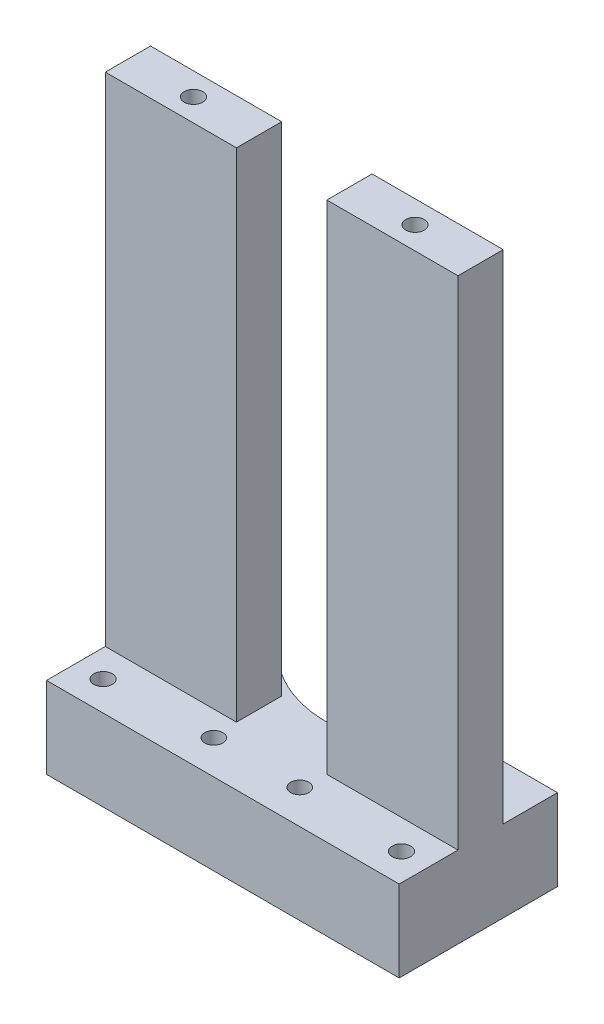
SolidWorks part; units mm, degrees
ref_plane "Ön Düzlem" through (0, 0, 0) normal (0, 0, 1) x (1, 0, 0)
ref_plane "Üst Düzlem" through (0, 0, 0) normal (0, 1, 0) x (1, 0, 0)
ref_plane "Sağ Düzlem" through (0, 0, 0) normal (1, 0, 0) x (0, 0, -1)
sketch "Çizim1" plane through (0, 0, 0) normal (0, 1, 0) x (1, 0, 0)
  line L3 (-39, 15) -> (-22, 15)
  line L5 (-39, 15) -> (-39, -20)
  line L6 (-39, -20) -> (39, -20)
  line L7 (39, 15) -> (39, -20)
  line L12 (22, 15) -> (39, 15)
  circle A0 centre (-29, 8) radius 2
  circle A1 centre (29, 8) radius 2
  arc A3 (-22, 15) -> (22, 15) centre (0, 29.1667) ccw
  circle A4 centre (-9.5, -12.5) radius 2
  circle A5 centre (9.5, -12.5) radius 2
  point P0 (0, 0)
  dimension "D1" = 78
extrude "Yükseklik-Ekstrüzyon1" add sketch "Çizim1" along normal blind 18
sketch "Çizim2" plane through (0, 18, 0) normal (0, 1, 0) x (1, 0, 0)
  line L0 (-39, 3) -> (-10, 3)
  line L1 (-39, 15) -> (-39, -20) construction
  line L2 (-39, 3) -> (-39, -7)
  line L3 (-10, 3) -> (-10, -7)
  line L4 (-10, -7) -> (-39, -7)
  line L10 (10, -7) -> (39, -7)
  line L11 (10, 3) -> (10, -7)
  line L12 (39, 3) -> (39, -7)
  line L13 (39, 3) -> (10, 3)
extrude "Yükseklik-Ekstrüzyon2" add sketch "Çizim2" along normal blind 110
sketch "Çizim3" plane through (0, 18, 0) normal (0, 1, 0) x (1, 0, 0)
  circle A0 centre (-33, -13.5) radius 2.05
  circle A2 centre (33, -13.5) radius 2.05
extrude "Kes-Ekstrüzyon1" cut sketch "Çizim3" against normal blind 6
sketch "Çizim4" plane through (0, 128, 0) normal (0, 1, 0) x (1, 0, 0)
  circle A0 centre (-24.5, -2) radius 2.05
  circle A2 centre (24.5, -2) radius 2.05
extrude "Kes-Ekstrüzyon2" cut sketch "Çizim4" against normal blind 30
sketch "Çizim5" plane through (0, 0, -3) normal (0, 0, -1) x (-1, 0, 0)
  line L2 (-21.5, 106.5) -> (-27.5, 109.5) construction
  line L3 (21.5, 109.5) -> (27.5, 109.5)
  line L4 (21.5, 109.5) -> (21.5, 106.5)
  line L5 (21.5, 106.5) -> (27.5, 106.5)
  line L6 (27.5, 109.5) -> (27.5, 106.5)
  line L7 (21.5, 109.5) -> (27.5, 106.5) construction
  line L8 (21.5, 106.5) -> (27.5, 109.5) construction
  line L9 (-21.5, 109.5) -> (-27.5, 106.5) construction
  line L10 (-27.5, 109.5) -> (-27.5, 106.5)
  line L11 (-21.5, 106.5) -> (-27.5, 106.5)
  line L12 (-21.5, 109.5) -> (-21.5, 106.5)
  line L13 (-21.5, 109.5) -> (-27.5, 109.5)
extrude "Kes-Ekstrüzyon3" cut sketch "Çizim5" against normal blind 9
